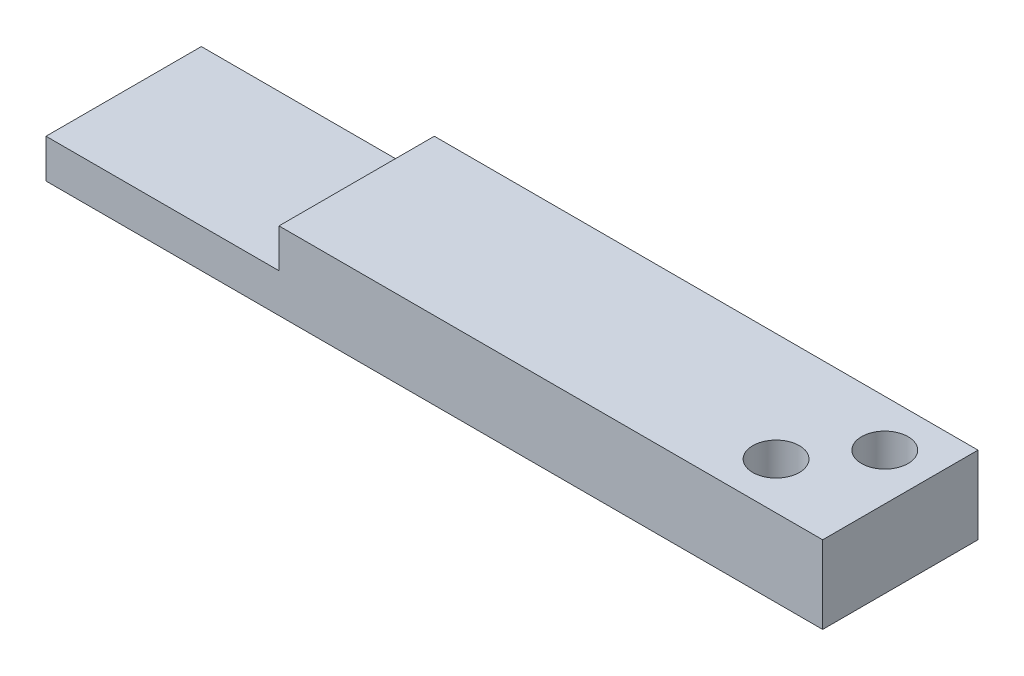
SolidWorks part; units mm, degrees
ref_plane "前视基准面" through (0, 0, 0) normal (0, 0, 1) x (1, 0, 0)
ref_plane "上视基准面" through (0, 0, 0) normal (0, 1, 0) x (1, 0, 0)
ref_plane "右视基准面" through (0, 0, 0) normal (1, 0, 0) x (0, 0, -1)
sketch "草图1" plane through (0, 0, 0) normal (0, 1, 0) x (1, 0, 0)
  line L1 (-25, -5) -> (25, -5)
  line L2 (-25, -5) -> (-25, 5)
  line L3 (-25, 5) -> (25, 5)
  line L4 (25, -5) -> (25, 5)
  line L5 (-25, -5) -> (25, 5) construction
  line L6 (-25, 5) -> (25, -5) construction
  point P0 (0, 0)
  dimension "D1" = 50
  dimension "D2" = 10
extrude "凸台-拉伸1" add sketch "草图1" along normal blind 5
sketch "草图2" plane through (0, 5, 0) normal (0, 1, 0) x (1, 0, 0)
  line L0 (25, 5) -> (-25, 5) construction
  line L1 (25, -5) -> (25, 5) construction
  line L2 (-25, -5) -> (25, -5) construction
  circle A0 centre (22, 2) radius 1.5
  circle A1 centre (19, -2) radius 1.5
  dimension "D1" = 3
  dimension "D2" = 3
  dimension "D3" = 3
  dimension "D4" = 6
  dimension "D5" = 3
  dimension "3" = 3
extrude "切除-拉伸1" cut sketch "草图2" against normal through all contours A0 | A1
sketch "草图3" plane through (0, 0, 5) normal (0, 0, 1) x (1, 0, 0)
  line L1 (-25, 5) -> (-10, 5)
  line L2 (-25, 5) -> (-25, 2.5)
  line L3 (-25, 2.5) -> (-10, 2.5)
  line L4 (-10, 5) -> (-10, 2.5)
  dimension "D1" = 2.5
  dimension "D2" = 15
extrude "切除-拉伸2" cut sketch "草图3" against normal through all
